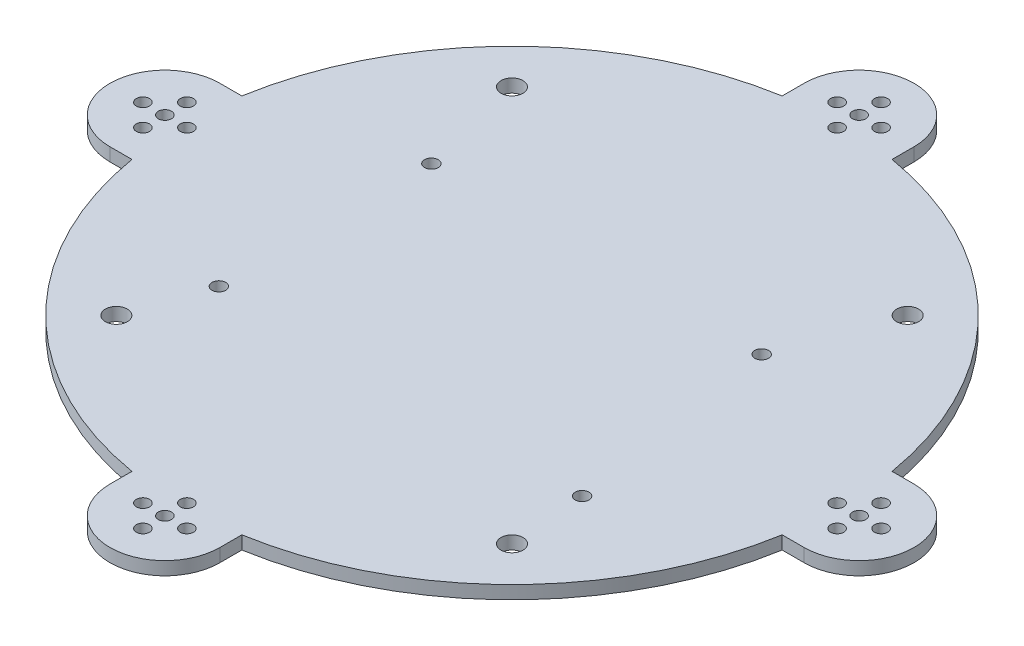
SolidWorks part; units mm, degrees
ref_plane "Front" through (0, 0, 0) normal (0, 0, 1) x (1, 0, 0)
ref_plane "Top" through (0, 0, 0) normal (0, 1, 0) x (1, 0, 0)
ref_plane "Right" through (0, 0, 0) normal (1, 0, 0) x (0, 0, -1)
sketch "Çizim1" plane through (0, 0, 0) normal (0, 1, 0) x (1, 0, 0)
  line L0 (-78.951, 12.5) -> (-73.951, 12.5)
  line L1 (-78.951, -12.5) -> (-73.951, -12.5)
  line L2 (-39.0616, -27.6168) -> (-39.0616, 22.2815) construction
  line L3 (12.5, 78.951) -> (12.5, 73.951)
  line L4 (-12.5, 78.951) -> (-12.5, 73.951)
  line L5 (78.951, -12.5) -> (73.951, -12.5)
  line L6 (78.951, 12.5) -> (73.951, 12.5)
  line L7 (-12.5, -78.951) -> (-12.5, -73.951)
  line L8 (12.5, -78.951) -> (12.5, -73.951)
  arc A0 (-78.951, 12.5) -> (-78.951, -12.5) centre (-78.951, 0) ccw
  circle A1 centre (-78.951, 0) radius 1.5
  circle A2 centre (-78.951, 5) radius 1.5
  circle A3 centre (-83.951, 0) radius 1.5
  circle A4 centre (-73.951, 0) radius 1.5
  circle A5 centre (-78.951, -5) radius 1.5
  circle A6 centre (36.0716, 20.7194) radius 1.5621
  circle A7 centre (43.5646, -27.6168) radius 1.5621
  circle A8 centre (-39.0616, -27.6168) radius 1.5621
  circle A9 centre (-39.0616, 20.7194) radius 1.5621
  arc A10 (12.5, 78.951) -> (-12.5, 78.951) centre (0, 78.951) ccw
  circle A11 centre (-5, 78.951) radius 1.5
  circle A12 centre (0, 78.951) radius 1.5
  circle A13 centre (0, 83.951) radius 1.5
  circle A14 centre (5, 78.951) radius 1.5
  circle A15 centre (0, 73.951) radius 1.5
  arc A16 (78.951, -12.5) -> (78.951, 12.5) centre (78.951, 0) ccw
  circle A17 centre (78.951, 5) radius 1.5
  circle A18 centre (78.951, 0) radius 1.5
  circle A19 centre (83.951, 0) radius 1.5
  circle A20 centre (78.951, -5) radius 1.5
  circle A21 centre (73.951, 0) radius 1.5
  arc A22 (-12.5, -78.951) -> (12.5, -78.951) centre (0, -78.951) ccw
  circle A23 centre (5, -78.951) radius 1.5
  circle A24 centre (0, -78.951) radius 1.5
  circle A25 centre (0, -83.951) radius 1.5
  circle A26 centre (-5, -78.951) radius 1.5
  circle A27 centre (0, -73.951) radius 1.5
  arc A28 (-73.951, -12.5) -> (-12.5, -73.951) centre (0, 0) ccw
  arc A29 (-12.5, 73.951) -> (-73.951, 12.5) centre (0, 0) ccw
  arc A30 (73.951, 12.5) -> (12.5, 73.951) centre (0, 0) ccw
  arc A31 (12.5, -73.951) -> (73.951, -12.5) centre (0, 0) ccw
  circle A32 centre (0, -73.951) radius 1.5 [skipped]
  circle A33 centre (0, -78.951) radius 1.5 [skipped]
  circle A34 centre (0, -83.951) radius 1.5 [skipped]
  circle A35 centre (-5, -78.951) radius 1.5 [skipped]
  circle A36 centre (5, -78.951) radius 1.5 [skipped]
  circle A37 centre (73.951, 0) radius 1.5 [skipped]
  circle A38 centre (78.951, 0) radius 1.5 [skipped]
  circle A39 centre (78.951, -5) radius 1.5 [skipped]
  circle A40 centre (78.951, 5) radius 1.5 [skipped]
  circle A41 centre (83.951, 0) radius 1.5 [skipped]
  circle A42 centre (0, 73.951) radius 1.5 [skipped]
  circle A43 centre (0, 78.951) radius 1.5 [skipped]
  circle A44 centre (5, 78.951) radius 1.5 [skipped]
  circle A45 centre (-5, 78.951) radius 1.5 [skipped]
  circle A46 centre (0, 83.951) radius 1.5 [skipped]
  circle A47 centre (45, 45) radius 2.5
  circle A48 centre (45, -45) radius 2.5
  circle A49 centre (-45, -45) radius 2.5
  circle A50 centre (-45, 45) radius 2.5
  point P3 (-90, 0)
  point P17 (29.9938, -21.3401)
  point P20 (29.9938, -21.3401)
  point P74 (0, 0)
  point P107 (0, 0)
  point P116 (0, 0)
  dimension "D3" = 12.5
  dimension "D5" = 3
  dimension "D6" = 3
  dimension "D7" = 3
  dimension "D8" = 5
  dimension "D13" = 3.1242
  dimension "D15" = 150
  dimension "D4" = 3
  dimension "D12" = 3
  dimension "D19" = 5
  dimension "D2" = 5
  dimension "D9" = 5
  dimension "D10" = 5
  dimension "D11" = 5
  dimension "D16" = 75.1332
  dimension "D17" = 4
  dimension "D18" = 4
  dimension "D20" = 45
  dimension "D21" = 45
  dimension "D14" = 82.6262
  dimension "D22" = 4
extrude "Yükseklik-Ekstrüzyon1" add sketch "Çizim1" along normal blind 3
